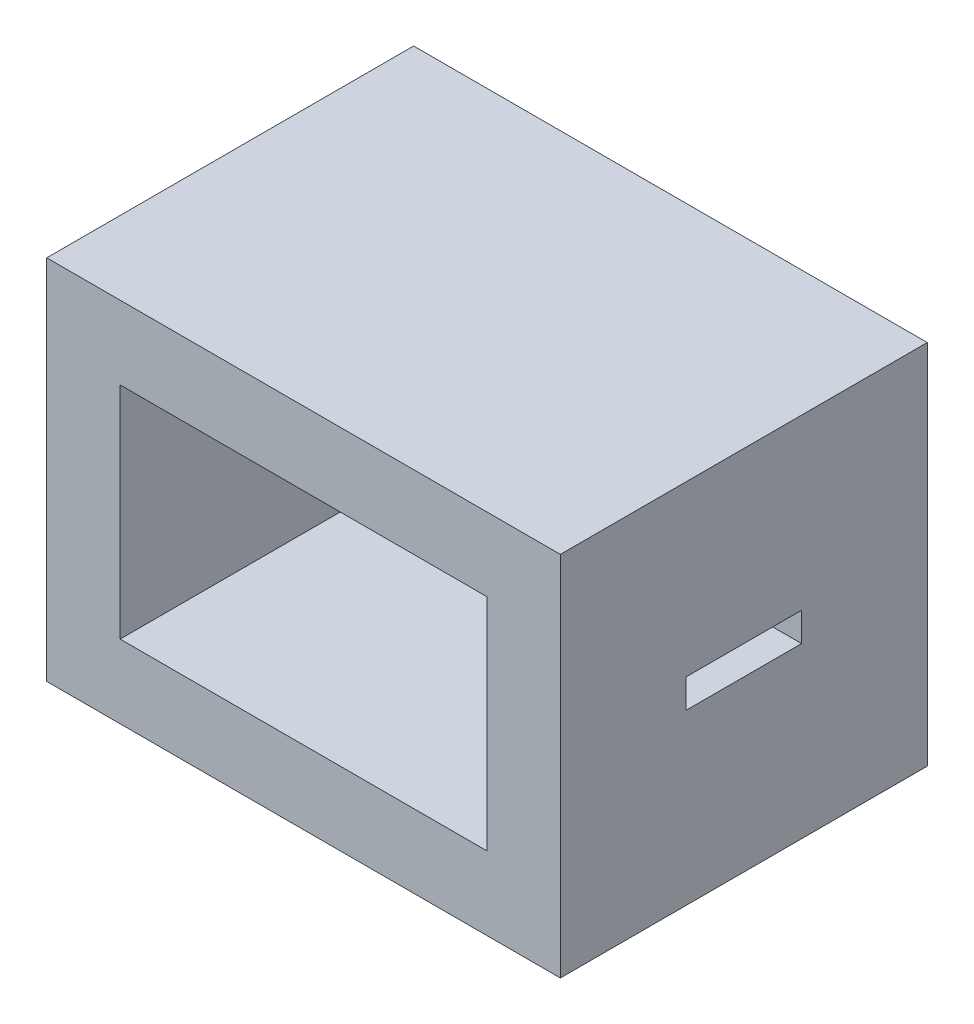
SolidWorks part; units mm, degrees
ref_plane "Front Plane" through (0, 0, 0) normal (0, 0, 1) x (1, 0, 0)
ref_plane "Top Plane" through (0, 0, 0) normal (0, 1, 0) x (1, 0, 0)
ref_plane "Right Plane" through (0, 0, 0) normal (1, 0, 0) x (0, 0, -1)
sketch "Çizim1" plane through (0, 0, 0) normal (1, 0, 0) x (0, 0, -1)
  line L1 (-6.35, 6.35) -> (6.35, 6.35)
  line L2 (-6.35, 6.35) -> (-6.35, -6.35)
  line L3 (-6.35, -6.35) -> (6.35, -6.35)
  line L4 (6.35, 6.35) -> (6.35, -6.35)
  line L5 (-6.35, 6.35) -> (6.35, -6.35) construction
  line L6 (-6.35, -6.35) -> (6.35, 6.35) construction
  point P0 (0, 0)
  dimension "D1" = 12.7
  dimension "D2" = 12.7
extrude "Yükseklik-Ekstrüzyon1" add sketch "Çizim1" along normal blind 2.54
sketch "Çizim2" plane through (2.54, 0, 0) normal (1, 0, 0) x (0, 0, -1)
  line L1 (-2, 0.5) -> (2, 0.5)
  line L2 (-2, 0.5) -> (-2, -0.5)
  line L3 (-2, -0.5) -> (2, -0.5)
  line L4 (2, 0.5) -> (2, -0.5)
  line L5 (-2, 0.5) -> (2, -0.5) construction
  line L6 (-2, -0.5) -> (2, 0.5) construction
  point P0 (0, 0)
  dimension "D1" = 4
  dimension "D2" = 1
extrude "Kes-Ekstrüzyon1" cut sketch "Çizim2" against normal blind 2.54
sketch "Çizim3" plane through (0, 6.35, 0) normal (0, 1, 0) x (1, 0, 0)
  line L1 (2.54, 6.35) -> (15.24, 6.35)
  line L2 (2.54, 6.35) -> (2.54, -6.35)
  line L3 (2.54, -6.35) -> (15.24, -6.35)
  line L4 (15.24, 6.35) -> (15.24, -6.35)
  dimension "D1" = 12.7
  dimension "D2" = 12.7
extrude "Yükseklik-Ekstrüzyon2" add sketch "Çizim3" against normal blind 2.54
sketch "Çizim4" plane through (0, -6.35, 0) normal (0, -1, 0) x (1, 0, 0)
  line L1 (2.54, 6.35) -> (15.24, 6.35)
  line L2 (2.54, 6.35) -> (2.54, -6.35)
  line L3 (2.54, -6.35) -> (15.24, -6.35)
  line L4 (15.24, 6.35) -> (15.24, -6.35)
extrude "Yükseklik-Ekstrüzyon3" add sketch "Çizim4" against normal blind 2.54
sketch "Çizim5" plane through (0, 0, -6.35) normal (0, 0, -1) x (-1, 0, 0)
  line L1 (-15.24, 3.81) -> (-2.54, 3.81)
  line L2 (-15.24, 3.81) -> (-15.24, -3.81)
  line L3 (-15.24, -3.81) -> (-2.54, -3.81)
  line L4 (-2.54, 3.81) -> (-2.54, -3.81)
extrude "Yükseklik-Ekstrüzyon4" add sketch "Çizim5" against normal blind 2.54
sketch "Çizim7" plane through (15.24, 0, 0) normal (1, 0, 0) x (0, 0, -1)
  line L1 (-6.35, 6.35) -> (6.35, 6.35)
  line L2 (-6.35, 6.35) -> (-6.35, -6.35)
  line L3 (-6.35, -6.35) -> (6.35, -6.35)
  line L4 (6.35, 6.35) -> (6.35, -6.35)
extrude "Yükseklik-Ekstrüzyon6" add sketch "Çizim7" along normal blind 2.54
sketch "Çizim8" plane through (15.24, 0, 0) normal (-1, 0, 0) x (0, 0, 1)
  line L1 (-2, 0.5) -> (2, 0.5)
  line L2 (-2, 0.5) -> (-2, -0.5)
  line L3 (-2, -0.5) -> (2, -0.5)
  line L4 (2, 0.5) -> (2, -0.5)
extrude "Kes-Ekstrüzyon2" cut sketch "Çizim8" against normal blind 2.54
